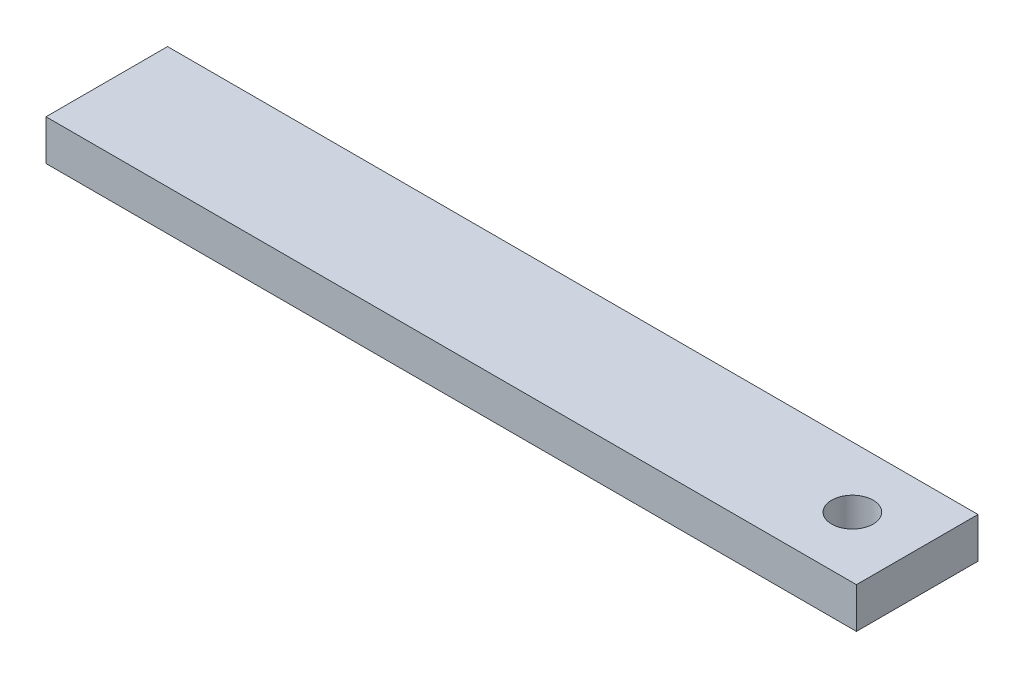
SolidWorks part; units mm, degrees
ref_plane "Front Plane" through (0, 0, 0) normal (0, 0, 1) x (1, 0, 0)
ref_plane "Top Plane" through (0, 0, 0) normal (0, 1, 0) x (1, 0, 0)
ref_plane "Right Plane" through (0, 0, 0) normal (1, 0, 0) x (0, 0, -1)
sketch "Sketch1" plane through (0, 0, 0) normal (0, 1, 0) x (1, 0, 0)
  line L1 (-100, -15) -> (100, -15)
  line L2 (-100, -15) -> (-100, 15)
  line L3 (-100, 15) -> (100, 15)
  line L4 (100, -15) -> (100, 15)
  line L5 (-100, -15) -> (100, 15) construction
  line L6 (-100, 15) -> (100, -15) construction
  point P0 (0, 0)
  dimension "D1" = 200
  dimension "D2" = 30
extrude "Boss-Extrude1" add sketch "Sketch1" along normal blind 10
sketch "Sketch2" plane through (0, 10, 0) normal (0, 1, 0) x (1, 0, 0)
  line L0 (100, -15) -> (100, 15) construction
  circle A0 centre (84, 0) radius 5.125
  dimension "D1" = 10.25
  dimension "D2" = 16
extrude "Cut-Extrude1" cut sketch "Sketch2" against normal through all
